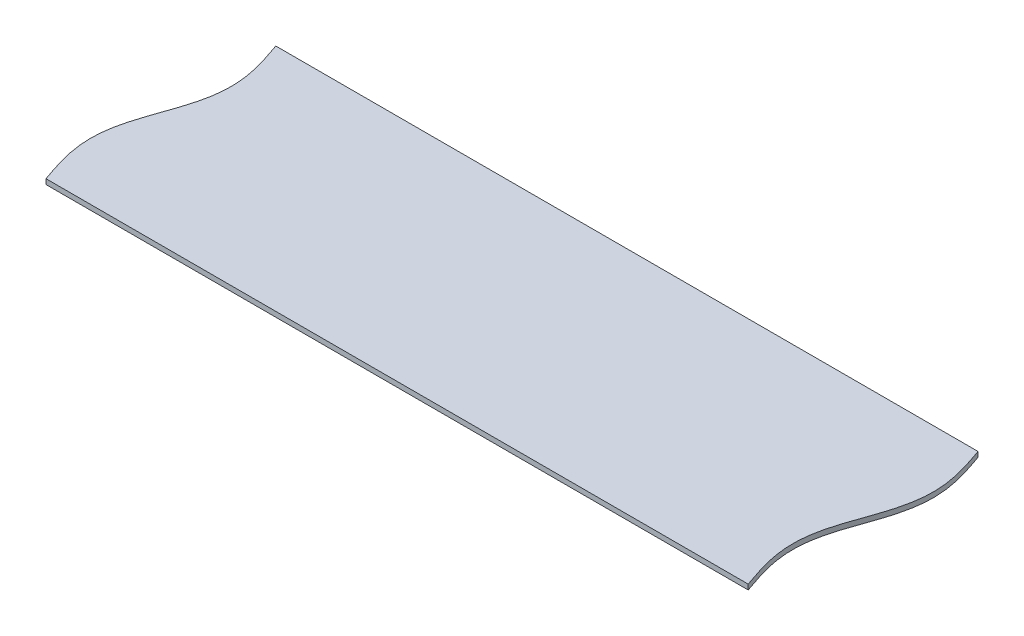
SolidWorks part; units mm, degrees
ref_plane "Front Plane" through (0, 0, 0) normal (0, 0, 1) x (1, 0, 0)
ref_plane "Top Plane" through (0, 0, 0) normal (0, 1, 0) x (1, 0, 0)
ref_plane "Right Plane" through (0, 0, 0) normal (1, 0, 0) x (0, 0, -1)
sketch "Sketch1" plane through (0, 0, 0) normal (0, 1, 0) x (1, 0, 0)
  line L0 (0, 0) -> (55, 0)
  line L2 (55, -18) -> (0, -18)
  spline S0 degree 4 poles (-0.5894, 1.8051) (-0.5748, 1.7527) (-0.5337, 1.6156) (-0.506, 1.5117) (-0.4082, 1.2075) (-0.3314, 0.9577) (-0.082, 0.2319) (0.0114, -0.0298) (0.3101, -0.8926) (0.4478, -1.3244) (0.6287, -1.9267) (0.76, -2.4502) (0.8864, -3.06) (0.9686, -3.6823) (1.0096, -4.326) (0.9972, -4.9609) (0.9377, -5.5988) (0.8323, -6.2274) (0.654, -7.0051) (0.3797, -7.9214) (0.0105, -8.9748) (-0.3629, -10.0341) (-0.6419, -10.9586) (-0.825, -11.7427) (-0.9327, -12.3804) (-0.9952, -13.0148) (-1.0076, -13.6555) (-0.9722, -14.2892) (-0.8963, -14.8497) (-0.8183, -15.2706) (-0.7435, -15.5964) (-0.6596, -15.9557) (-0.5019, -16.5014) (-0.3736, -16.9218) (-0.0327, -17.9095) (0.0764, -18.2153) (0.3497, -19.0099) (0.4157, -19.2312) (0.5015, -19.5002) (0.5215, -19.5726) (0.5504, -19.6686) (0.5666, -19.7244) (0.5744, -19.7517) knots 0 0 0 0 0 0.010336 0.020671 0.031007 0.041343 0.082685 0.111326 0.139968 0.16251 0.185053 0.213694 0.242335 0.270977 0.299618 0.328259 0.3569 0.385541 0.414183 0.471334 0.528617 0.585899 0.615913 0.644554 0.673195 0.701836 0.730477 0.759119 0.78776 0.80208 0.809241 0.816401 0.859983 0.888625 0.917266 0.958633 0.979316 0.984487 0.989658 0.994829 1 1 1 1 1 construction
  spline S1 degree 4 poles (0, 0) (0.0397, -0.1136) (0.1278, -0.3663) (0.3141, -0.9051) (0.4478, -1.3244) (0.6287, -1.9267) (0.76, -2.4502) (0.8864, -3.06) (0.9686, -3.6823) (1.0096, -4.326) (0.9972, -4.9609) (0.9377, -5.5988) (0.8323, -6.2274) (0.654, -7.0051) (0.3797, -7.9214) (0.0105, -8.9748) (-0.3629, -10.0341) (-0.6419, -10.9586) (-0.825, -11.7427) (-0.9327, -12.3804) (-0.9952, -13.0148) (-1.0076, -13.6555) (-0.9722, -14.2892) (-0.8963, -14.8497) (-0.8183, -15.2706) (-0.7435, -15.5964) (-0.6596, -15.9557) (-0.5019, -16.5014) (-0.3736, -16.9218) (-0.1318, -17.6223) (-0.0439, -17.8743) (0, -18) knots 0.085662 0.085662 0.085662 0.085662 0.085662 0.111326 0.139968 0.16251 0.185053 0.213694 0.242335 0.270977 0.299618 0.328259 0.3569 0.385541 0.414183 0.471334 0.528617 0.585899 0.615913 0.644554 0.673195 0.701836 0.730477 0.759119 0.78776 0.80208 0.809241 0.816401 0.859983 0.888625 0.917266 0.917266 0.917266 0.917266 0.917266
  spline S2 degree 4 poles (54.4106, 1.8051) (54.4252, 1.7527) (54.4663, 1.6156) (54.494, 1.5117) (54.5918, 1.2075) (54.6686, 0.9577) (54.918, 0.2319) (55.0114, -0.0298) (55.3101, -0.8926) (55.4478, -1.3244) (55.6287, -1.9267) (55.76, -2.4502) (55.8864, -3.06) (55.9686, -3.6823) (56.0096, -4.326) (55.9972, -4.9609) (55.9377, -5.5988) (55.8323, -6.2274) (55.654, -7.0051) (55.3797, -7.9214) (55.0105, -8.9748) (54.6371, -10.0341) (54.3581, -10.9586) (54.175, -11.7427) (54.0673, -12.3804) (54.0048, -13.0148) (53.9924, -13.6555) (54.0278, -14.2892) (54.1037, -14.8497) (54.1817, -15.2706) (54.2565, -15.5964) (54.3404, -15.9557) (54.4981, -16.5014) (54.6264, -16.9218) (54.9673, -17.9095) (55.0764, -18.2153) (55.3497, -19.0099) (55.4157, -19.2312) (55.5015, -19.5002) (55.5215, -19.5726) (55.5504, -19.6686) (55.5666, -19.7244) (55.5744, -19.7517) knots 0 0 0 0 0 0.010336 0.020671 0.031007 0.041343 0.082685 0.111326 0.139968 0.16251 0.185053 0.213694 0.242335 0.270977 0.299618 0.328259 0.3569 0.385541 0.414183 0.471334 0.528617 0.585899 0.615913 0.644554 0.673195 0.701836 0.730477 0.759119 0.78776 0.80208 0.809241 0.816401 0.859983 0.888625 0.917266 0.958633 0.979316 0.984487 0.989658 0.994829 1 1 1 1 1 construction
  spline S3 degree 4 poles (55, 0) (55.0397, -0.1136) (55.1278, -0.3663) (55.3141, -0.9051) (55.4478, -1.3244) (55.6287, -1.9267) (55.76, -2.4502) (55.8864, -3.06) (55.9686, -3.6823) (56.0096, -4.326) (55.9972, -4.9609) (55.9377, -5.5988) (55.8323, -6.2274) (55.654, -7.0051) (55.3797, -7.9214) (55.0105, -8.9748) (54.6371, -10.0341) (54.3581, -10.9586) (54.175, -11.7427) (54.0673, -12.3804) (54.0048, -13.0148) (53.9924, -13.6555) (54.0278, -14.2892) (54.1037, -14.8497) (54.1817, -15.2706) (54.2565, -15.5964) (54.3404, -15.9557) (54.4981, -16.5014) (54.6264, -16.9218) (54.8682, -17.6223) (54.9561, -17.8743) (55, -18) knots 0.085662 0.085662 0.085662 0.085662 0.085662 0.111326 0.139968 0.16251 0.185053 0.213694 0.242335 0.270977 0.299618 0.328259 0.3569 0.385541 0.414183 0.471334 0.528617 0.585899 0.615913 0.644554 0.673195 0.701836 0.730477 0.759119 0.78776 0.80208 0.809241 0.816401 0.859983 0.888625 0.917266 0.917266 0.917266 0.917266 0.917266
  point P3 (54.5333, 0)
  point P4 (0, 0)
  dimension "D4" = 18
  dimension "D5" = 55
extrude "Boss-Extrude1" add sketch "Sketch1" along normal blind 0.4
